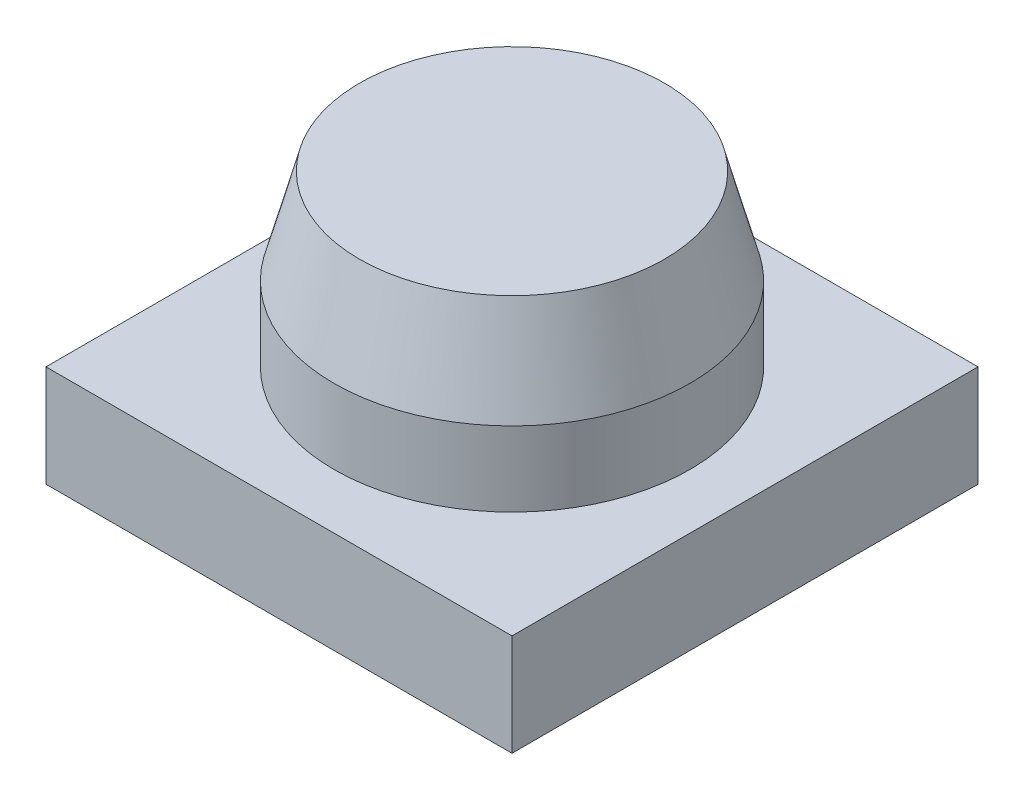
SolidWorks part; units mm, degrees
ref_plane "Front Plane" through (0, 0, 0) normal (0, 0, 1) x (1, 0, 0)
ref_plane "Top Plane" through (0, 0, 0) normal (0, 1, 0) x (1, 0, 0)
ref_plane "Right Plane" through (0, 0, 0) normal (1, 0, 0) x (0, 0, -1)
sketch "Sketch1" plane through (0, 0, 0) normal (0, 1, 0) x (1, 0, 0)
  line L1 (-2.75, -2.75) -> (2.75, -2.75)
  line L2 (-2.75, -2.75) -> (-2.75, 2.75)
  line L3 (-2.75, 2.75) -> (2.75, 2.75)
  line L4 (2.75, -2.75) -> (2.75, 2.75)
  line L5 (-2.75, -2.75) -> (2.75, 2.75) construction
  line L6 (-2.75, 2.75) -> (2.75, -2.75) construction
  point P0 (0, 0)
  dimension "D1" = 5.5
  dimension "D2" = 5.5
extrude "Boss-Extrude1" add sketch "Sketch1" along normal blind 1.2
sketch "Sketch2" plane through (0, 1.2, 0) normal (0, 1, 0) x (1, 0, 0)
  circle A0 centre (0, 0) radius 2.1
  dimension "D1" = 4.2
extrude "Boss-Extrude2" add sketch "Sketch2" along normal blind 2
sketch "Sketch3" plane through (0, 0, 0) normal (0, -1, 0) x (1, 0, 0)
  circle A0 centre (0, 0) radius 1.95
  dimension "D1" = 3.9
extrude "Cut-Extrude1" cut sketch "Sketch3" against normal blind 0.9
chamfer "Chamfer1" [suppressed] distance 0.5 angle 45
chamfer "Chamfer2" distance 0.3 angle 75 1 edges at (0, 3.2, 2.1)
